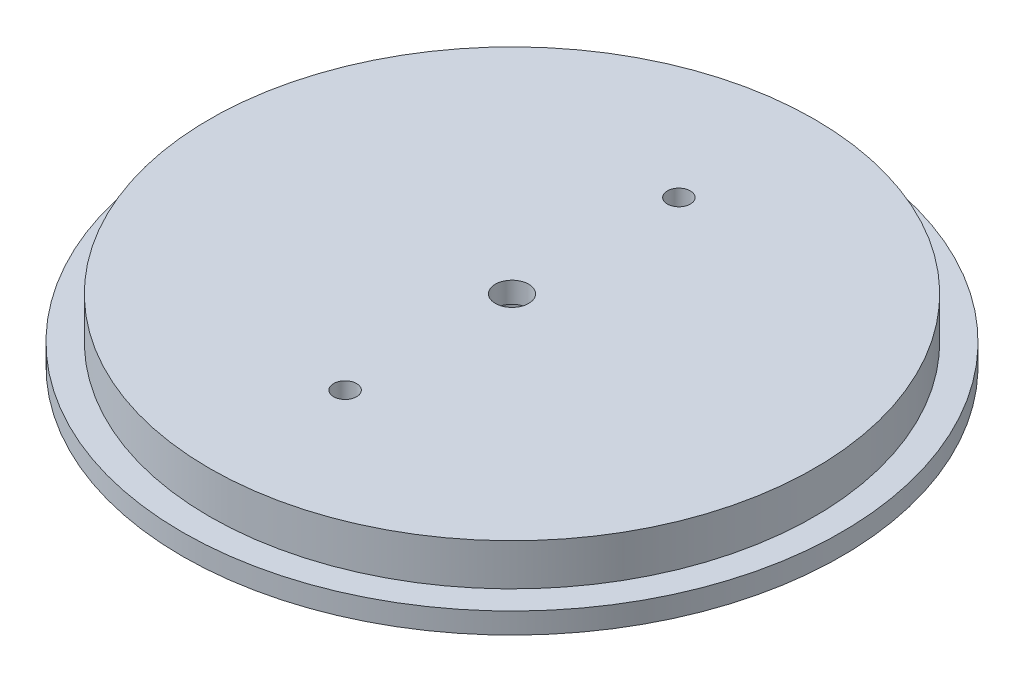
SolidWorks part; units mm, degrees
ref_plane "Front Plane" through (0, 0, 0) normal (0, 0, 1) x (1, 0, 0)
ref_plane "Top Plane" through (0, 0, 0) normal (0, 1, 0) x (1, 0, 0)
ref_plane "Right Plane" through (0, 0, 0) normal (1, 0, 0) x (0, 0, -1)
sketch "Sketch1" plane through (0, 0, 0) normal (0, 1, 0) x (1, 0, 0)
  circle A0 centre (0, 0) radius 79
  dimension "D1" = 158
extrude "Boss-Extrude1" add sketch "Sketch1" along normal blind 5
sketch "Sketch2" plane through (0, 5, 0) normal (0, 1, 0) x (1, 0, 0)
  circle A0 centre (0, 0) radius 72.5
  dimension "D1" = 145
extrude "Boss-Extrude2" add sketch "Sketch2" along normal blind 10
sketch "Sketch3" plane through (0, 15, 0) normal (0, 1, 0) x (1, 0, 0)
  line L0 (0, 0) -> (0, 40) construction
  line L1 (0, 0) -> (0, -40) construction
  circle A0 centre (0, 40) radius 2.75
  circle A1 centre (0, -40) radius 2.75
  dimension "D3" = 5.5
  dimension "D4" = 5.5
  dimension "D1" = 40
  dimension "D2" = 40
extrude "Cut-Extrude1" cut sketch "Sketch3" against normal through all
sketch "Sketch4" plane through (0, 15, 0) normal (0, 1, 0) x (1, 0, 0)
  circle A0 centre (0, 0) radius 4
  dimension "D1" = 8
extrude "Cut-Extrude2" cut sketch "Sketch4" against normal blind 5
sketch "Sketch5" plane through (0, 0, 0) normal (0, -1, 0) x (1, 0, 0)
  circle A0 centre (0, 0) radius 6
  dimension "D1" = 12
extrude "Cut-Extrude3" cut sketch "Sketch5" against normal blind 10
